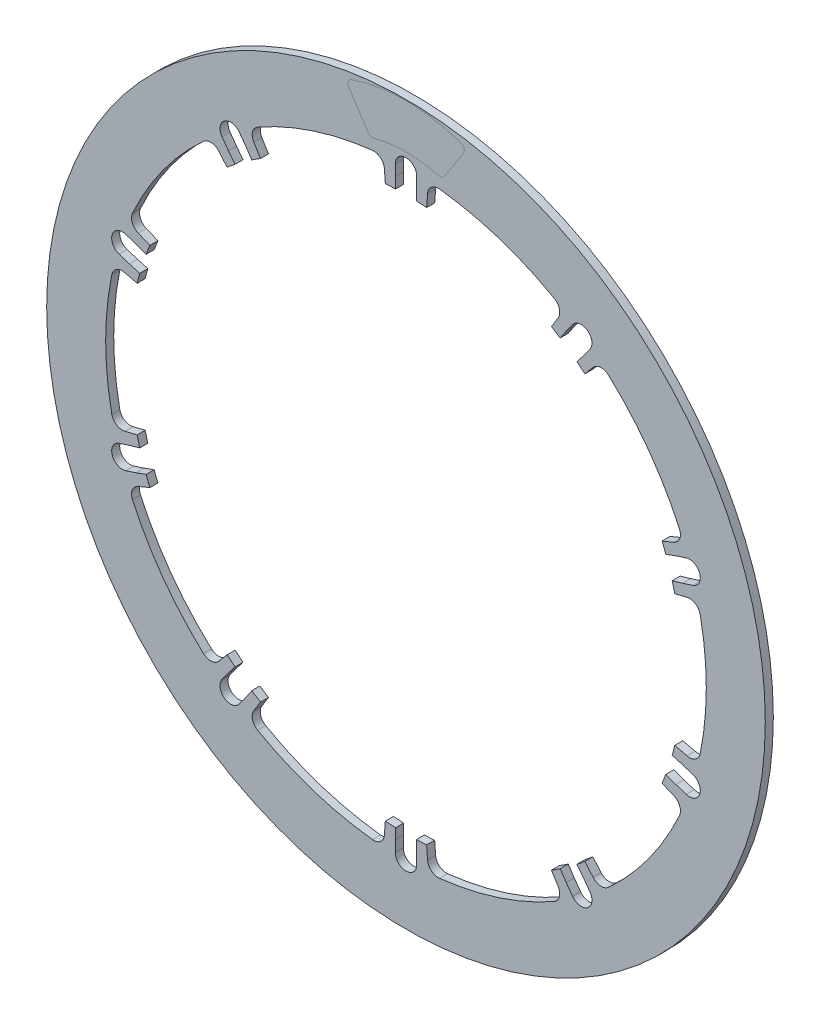
SolidWorks part; units mm, degrees
material "Gray Cast Iron"
ref_plane "Front Plane" through (0, 0, 0) normal (0, 0, 1) x (1, 0, 0)
ref_plane "Top Plane" through (0, 0, 0) normal (0, 1, 0) x (1, 0, 0)
ref_plane "Right Plane" through (0, 0, 0) normal (1, 0, 0) x (0, 0, -1)
sketch "Sketch1" plane through (0, 0, 0) normal (0, 0, 1) x (1, 0, 0)
  circle A0 centre (0, 0) radius 212.725
  dimension "D1" = 425.45
extrude "Boss-Extrude1" add sketch "Sketch1" along normal blind 4.7625
sketch3d "3DSketch3" [suppressed]
  line L4 (22.632, 184.3324, 30.7403) -> (33.9015, 201.686, 30.7403)
  line L5 (-33.9015, 201.686, 30.7403) -> (-22.632, 184.3324, 30.7403)
  arc A2 (-19.1346, 182.9983, 30.7403) -> (19.1346, 182.9983, 30.7403) centre (0, 112.7617, 30.7403) ccw
  spline S10 degree 3 poles (-22.632, 184.3324, 30.7403) (-22.5988, 184.2811, 30.7403) (-22.5293, 184.1805, 30.7403) (-22.4165, 184.0361, 30.7403) (-22.2957, 183.8983, 30.7403) (-22.1669, 183.7678, 30.7403) (-22.0309, 183.6449, 30.7403) (-21.8881, 183.53, 30.7403) (-21.7389, 183.4235, 30.7403) (-21.5838, 183.3258, 30.7403) (-21.4233, 183.2372, 30.7403) (-21.258, 183.1581, 30.7403) (-21.0428, 183.0698, 30.7403) (-20.7737, 182.9843, 30.7403) (-20.4488, 182.9172, 30.7403) (-20.1187, 182.8844, 30.7403) (-19.7871, 182.8865, 30.7403) (-19.4572, 182.9221, 30.7403) (-19.2411, 182.9691, 30.7403) (-19.1346, 182.9983, 30.7403) knots 0 0 0 0 0.045782 0.091558 0.137334 0.183113 0.228892 0.274672 0.32045 0.366227 0.412004 0.457782 0.503559 0.586301 0.669039 0.751777 0.834518 0.917255 1 1 1 1
  spline S11 degree 3 poles (19.1346, 182.9983, 30.7403) (19.1932, 182.9822, 30.7403) (19.3112, 182.9536, 30.7403) (19.4903, 182.9212, 30.7403) (19.6709, 182.8988, 30.7403) (19.8526, 182.8871, 30.7403) (20.0347, 182.8856, 30.7403) (20.2165, 182.8946, 30.7403) (20.3976, 182.9139, 30.7403) (20.5772, 182.9436, 30.7403) (20.7548, 182.9836, 30.7403) (20.9299, 183.0336, 30.7403) (21.1494, 183.1103, 30.7403) (21.4086, 183.2251, 30.7403) (21.6981, 183.3917, 30.7403) (21.9686, 183.5877, 30.7403) (22.2165, 183.8112, 30.7403) (22.4407, 184.059, 30.7403) (22.5716, 184.239, 30.7403) (22.632, 184.3324, 30.7403) knots 0 0 0 0 0.045473 0.090941 0.136409 0.181879 0.227351 0.272822 0.318291 0.36376 0.409229 0.454698 0.500168 0.583473 0.666777 0.750082 0.83339 0.916693 1 1 1 1
  spline S12 degree 3 poles (33.9015, 201.686, 30.7403) (33.9344, 201.7364, 30.7403) (33.9971, 201.839, 30.7403) (34.0817, 201.9976, 30.7403) (34.1575, 202.1609, 30.7403) (34.2237, 202.3283, 30.7403) (34.2804, 202.4992, 30.7403) (34.3274, 202.6731, 30.7403) (34.3646, 202.8492, 30.7403) (34.3917, 203.0273, 30.7403) (34.4086, 203.2065, 30.7403) (34.4153, 203.3864, 30.7403) (34.4119, 203.5665, 30.7403) (34.3756, 204.0435, 30.7403) (34.1614, 204.8075, 30.7403) (33.6821, 205.4852, 30.7403) (33.2752, 205.8566, 30.7403) (33.0454, 206.0314, 30.7403) (32.8006, 206.1843, 30.7403) (32.5436, 206.3149, 30.7403) (32.3643, 206.3858, 30.7403) (32.2732, 206.417, 30.7403) knots 0 0 0 0 0.031297 0.062588 0.093878 0.12517 0.156463 0.187756 0.219048 0.250339 0.28163 0.312921 0.344212 0.375504 0.562427 0.749344 0.799474 0.849606 0.899737 0.949865 1 1 1 1
  spline S13 degree 3 poles (32.2732, 206.417, 30.7403) (31.9592, 206.5252, 30.7403) (31.3303, 206.7384, 30.7403) (30.3838, 207.0486, 30.7403) (29.4343, 207.3495, 30.7403) (28.4817, 207.6406, 30.7403) (27.5262, 207.9222, 30.7403) (26.568, 208.1942, 30.7403) (25.6071, 208.4564, 30.7403) (24.6436, 208.7091, 30.7403) (23.6776, 208.952, 30.7403) (22.7092, 209.1852, 30.7403) (21.7385, 209.4087, 30.7403) (20.7656, 209.6224, 30.7403) (19.7906, 209.8263, 30.7403) (18.8136, 210.0204, 30.7403) (17.8348, 210.2046, 30.7403) (16.8541, 210.3791, 30.7403) (15.8717, 210.5436, 30.7403) (14.8877, 210.6982, 30.7403) (13.9022, 210.843, 30.7403) (12.9153, 210.9778, 30.7403) (11.927, 211.1027, 30.7403) (9.4532, 211.3901, 30.7403) (5.4798, 211.7206, 30.7403) (0, 211.8722, 30.7403) (-5.4798, 211.7206, 30.7403) (-9.7842, 211.3626, 30.7403) (-12.9159, 210.9828, 30.7403) (-14.8884, 210.7032, 30.7403) (-16.8549, 210.384, 30.7403) (-18.8146, 210.0253, 30.7403) (-20.7667, 209.6273, 30.7403) (-22.7103, 209.1901, 30.7403) (-24.6448, 208.7139, 30.7403) (-26.5694, 208.1991, 30.7403) (-28.483, 207.645, 30.7403) (-30.3853, 207.0535, 30.7403) (-31.6453, 206.6334, 30.7403) (-32.2732, 206.417, 30.7403) knots 0 0 0 0 0.015151 0.030302 0.045452 0.060603 0.075754 0.090905 0.106056 0.121206 0.136357 0.151508 0.166659 0.18181 0.19696 0.212111 0.227262 0.242413 0.257563 0.272714 0.287865 0.303016 0.318167 0.333317 0.41666 0.500002 0.583344 0.666687 0.696988 0.727289 0.75759 0.787892 0.818193 0.848494 0.878795 0.909096 0.939398 0.969699 1 1 1 1
  spline S14 degree 3 poles (-32.2732, 206.417, 30.7403) (-32.33, 206.3976, 30.7403) (-32.4424, 206.3554, 30.7403) (-32.6063, 206.2826, 30.7403) (-32.7663, 206.2007, 30.7403) (-32.9213, 206.1097, 30.7403) (-33.071, 206.0102, 30.7403) (-33.2148, 205.9024, 30.7403) (-33.3523, 205.7867, 30.7403) (-33.4831, 205.6634, 30.7403) (-33.6067, 205.5329, 30.7403) (-33.7226, 205.3956, 30.7403) (-33.8307, 205.2519, 30.7403) (-34.0967, 204.8533, 30.7403) (-34.3994, 204.1174, 30.7403) (-34.4385, 203.2861, 30.7403) (-34.346, 202.7423, 30.7403) (-34.2724, 202.4636, 30.7403) (-34.1736, 202.193, 30.7403) (-34.0515, 201.9325, 30.7403) (-33.9541, 201.7665, 30.7403) (-33.9015, 201.686, 30.7403) knots 0 0 0 0 0.031241 0.062476 0.093711 0.124947 0.156184 0.187421 0.218658 0.249893 0.281128 0.312363 0.343599 0.374835 0.562326 0.749809 0.799846 0.849885 0.899924 0.949958 1 1 1 1
  point P8 (0, 112.7617, -42.0561)
sketch "Sketch4" plane through (0, 0, 4.7625) normal (0, 0, 1) x (1, 0, 0)
  line L2 (22.7365, 184.6731) -> (34.006, 202.0267)
  line L3 (-33.7971, 202.0267) -> (-22.5275, 184.6731)
  arc A1 (19.2391, 183.339) -> (-19.0302, 183.339) centre (0.1045, 113.1023) ccw
  spline S5 degree 3 poles (34.006, 202.0267) (34.0389, 202.0771) (34.1016, 202.1797) (34.1862, 202.3383) (34.262, 202.5016) (34.3282, 202.669) (34.4038, 202.8969) (34.46, 203.1306) (34.4962, 203.3679) (34.5131, 203.5472) (34.5198, 203.7271) (34.5163, 203.9072) (34.4801, 204.3842) (34.2659, 205.1481) (33.7866, 205.8259) (33.3797, 206.1973) (33.1498, 206.3721) (32.9051, 206.525) (32.648, 206.6556) (32.4688, 206.7265) (32.3776, 206.7577) knots 0 0 0 0 0.031297 0.062588 0.093878 0.12517 0.156463 0.219048 0.250339 0.28163 0.312921 0.344212 0.375504 0.562427 0.749344 0.799474 0.849606 0.899737 0.949865 1 1 1 1
  spline S6 degree 3 poles (19.2391, 183.339) (19.2977, 183.3229) (19.4156, 183.2943) (19.5948, 183.2619) (19.7754, 183.2395) (19.9571, 183.2278) (20.1392, 183.2263) (20.321, 183.2353) (20.5021, 183.2546) (20.7416, 183.2942) (20.9771, 183.3543) (21.2539, 183.451) (21.5131, 183.5658) (21.8026, 183.7323) (22.073, 183.9284) (22.321, 184.1519) (22.5452, 184.3996) (22.6761, 184.5797) (22.7365, 184.6731) knots 0 0 0 0 0.045473 0.090941 0.136409 0.181879 0.227351 0.272822 0.318291 0.36376 0.454698 0.500168 0.583473 0.666777 0.750082 0.83339 0.916693 1 1 1 1
  spline S7 degree 3 poles (-22.5275, 184.6731) (-22.4943, 184.6218) (-22.4249, 184.5212) (-22.312, 184.3768) (-22.1912, 184.239) (-22.0624, 184.1085) (-21.9264, 183.9856) (-21.7836, 183.8707) (-21.6344, 183.7642) (-21.4276, 183.6339) (-21.2101, 183.5219) (-20.9383, 183.4105) (-20.6692, 183.325) (-20.3444, 183.2579) (-20.0142, 183.225) (-19.6827, 183.2272) (-19.3527, 183.2628) (-19.1367, 183.3098) (-19.0302, 183.339) knots 0 0 0 0 0.045782 0.091558 0.137334 0.183113 0.228892 0.274672 0.32045 0.366227 0.457782 0.503559 0.586301 0.669039 0.751777 0.834518 0.917255 1 1 1 1
  spline S8 degree 3 poles (-32.1687, 206.7577) (-32.2255, 206.7383) (-32.3379, 206.6961) (-32.5019, 206.6233) (-32.6618, 206.5414) (-32.8168, 206.4504) (-33.0164, 206.3177) (-33.2043, 206.1685) (-33.3786, 206.0041) (-33.5022, 205.8736) (-33.6182, 205.7363) (-33.7262, 205.5926) (-33.9922, 205.194) (-34.2949, 204.4581) (-34.3341, 203.6268) (-34.2415, 203.083) (-34.1679, 202.8043) (-34.0691, 202.5337) (-33.947, 202.2732) (-33.8496, 202.1072) (-33.7971, 202.0267) knots 0 0 0 0 0.031241 0.062476 0.093711 0.124947 0.156184 0.218658 0.249893 0.281128 0.312363 0.343599 0.374835 0.562326 0.749809 0.799846 0.849885 0.899924 0.949958 1 1 1 1
  spline S9 degree 3 poles (32.3776, 206.7577) (32.0637, 206.8659) (31.4348, 207.0791) (30.4883, 207.3893) (29.5388, 207.6902) (28.5862, 207.9813) (26.9938, 208.4506) (23.7904, 209.325) (20.2255, 210.1269) (16.6328, 210.7845) (14.6646, 211.0938) (13.0197, 211.3185) (12.0315, 211.4434) (9.5577, 211.7308) (5.5843, 212.0613) (0.1045, 212.2129) (-5.3753, 212.0613) (-9.6798, 211.7033) (-12.8114, 211.3235) (-14.7839, 211.0439) (-16.7504, 210.7247) (-18.7101, 210.366) (-20.6622, 209.968) (-22.6058, 209.5308) (-24.5403, 209.0546) (-26.4649, 208.5398) (-28.3785, 207.9857) (-30.2808, 207.3942) (-31.5409, 206.9741) (-32.1687, 206.7577) knots 0 0 0 0 0.015151 0.030302 0.045452 0.060603 0.075754 0.121206 0.212111 0.242413 0.287865 0.303016 0.318167 0.333317 0.41666 0.500002 0.583344 0.666687 0.696988 0.727289 0.75759 0.787892 0.818193 0.848494 0.878795 0.909096 0.939398 0.969699 1 1 1 1
sketch "Sketch6" plane through (0, 0, 0) normal (0, 0, -1) x (-1, 0, 0)
  line L0 (-22.7365, 184.6731) -> (-34.006, 202.0267) construction
  line L1 (33.7971, 202.0267) -> (22.5275, 184.6731) construction
  line L2 (-22.7365, 184.6731) -> (-34.006, 202.0267)
  line L3 (33.7971, 202.0267) -> (22.5275, 184.6731)
  arc A0 (19.0302, 183.339) -> (-19.2391, 183.339) centre (-0.1045, 113.1023) ccw construction
  circle A1 centre (0, 0) radius 212.725
  circle A2 centre (0, 0) radius 212.725
  arc A3 (19.0302, 183.339) -> (-19.2391, 183.339) centre (-0.1045, 113.1023) ccw
  spline S0 degree 3 poles (-2016.3209, 153.4131) (-13.1774, 313.7756) (-3.6105, 186.1555) (-19.5948, 183.2619) (-19.7754, 183.2395) (-19.9571, 183.2278) (-20.1392, 183.2263) (-20.321, 183.2353) (-20.5021, 183.2546) (-20.7416, 183.2942) (-20.9771, 183.3543) (-21.2539, 183.451) (-21.5131, 183.5658) (-21.8026, 183.7323) (-22.073, 183.9284) (-22.321, 184.1519) (-33.7349, 196.7661) (61.8944, 295.2324) (1583.0626, -1002.353) knots -12.036429 -12.036429 -12.036429 -12.036429 0.045473 0.090941 0.136409 0.181879 0.227351 0.272822 0.318291 0.36376 0.454698 0.500168 0.583473 0.666777 0.750082 0.83339 0.916693 13.47468 13.47468 13.47468 13.47468 only from (-19.2391, 183.339) to (-22.7365, 184.6731) construction
  spline S1 degree 3 poles (-741.6985, 2071.3636) (51.5513, 215.3428) (-28.083, 190.8965) (-34.1862, 202.3383) (-34.262, 202.5016) (-34.3282, 202.669) (-34.4038, 202.8969) (-34.46, 203.1306) (-34.4962, 203.3679) (-34.5131, 203.5472) (-34.5198, 203.7271) (-34.5163, 203.9072) (-34.4801, 204.3842) (-34.2659, 205.1481) (-33.7866, 205.8259) (-33.3797, 206.1973) (-33.1498, 206.3721) (-32.9051, 206.525) (-19.4783, 213.3465) (41.9008, 122.514) (-1615.5521, -1012.0405) knots -6.679954 -6.679954 -6.679954 -6.679954 0.031297 0.062588 0.093878 0.12517 0.156463 0.219048 0.250339 0.28163 0.312921 0.344212 0.375504 0.562427 0.749344 0.799474 0.849606 0.899737 0.949865 8.706653 8.706653 8.706653 8.706653 only from (-34.006, 202.0267) to (-32.3776, 206.7577) construction
  spline S2 degree 3 poles (1661.243, 1259.3746) (-203.7859, -162.5293) (-163.0238, 163.9576) (-30.4883, 207.3893) (-29.5388, 207.6902) (-28.5862, 207.9813) (-26.9938, 208.4506) (-23.7904, 209.325) (-20.2255, 210.1269) (-16.6328, 210.7845) (-14.6646, 211.0938) (-13.0197, 211.3185) (-12.0315, 211.4434) (-9.5577, 211.7308) (-5.5843, 212.0613) (-0.1045, 212.2129) (5.3753, 212.0613) (9.6798, 211.7033) (12.8114, 211.3235) (14.7839, 211.0439) (16.7504, 210.7247) (18.7101, 210.366) (20.6622, 209.968) (22.6058, 209.5308) (24.5403, 209.0546) (26.4649, 208.5398) (28.3785, 207.9857) (189.3327, 157.9434) (218.1983, -304.2931) (-1891.4217, 643.6889) knots -6.319065 -6.319065 -6.319065 -6.319065 0.015151 0.030302 0.045452 0.060603 0.075754 0.121206 0.212111 0.242413 0.287865 0.303016 0.318167 0.333317 0.41666 0.500002 0.583344 0.666687 0.696988 0.727289 0.75759 0.787892 0.818193 0.848494 0.878795 0.909096 0.939398 0.969699 8.600273 8.600273 8.600273 8.600273 only from (-32.3776, 206.7577) to (32.1687, 206.7577) construction
  spline S3 degree 3 poles (1741.3262, -829.6052) (-26.9574, 143.7974) (20.6648, 211.8759) (32.5019, 206.6233) (32.6618, 206.5414) (32.8168, 206.4504) (33.0164, 206.3177) (33.2043, 206.1685) (33.3786, 206.0041) (33.5022, 205.8736) (33.6182, 205.7363) (33.7262, 205.5926) (33.9922, 205.194) (34.2949, 204.4581) (34.3341, 203.6268) (34.2415, 203.083) (34.1679, 202.8043) (34.0691, 202.5337) (27.687, 188.9067) (-76.4304, 222.6453) (533.1826, 2136.6237) knots -6.671073 -6.671073 -6.671073 -6.671073 0.031241 0.062476 0.093711 0.124947 0.156184 0.218658 0.249893 0.281128 0.312363 0.343599 0.374835 0.562326 0.749809 0.799846 0.849885 0.899924 0.949958 8.70048 8.70048 8.70048 8.70048 only from (32.1687, 206.7577) to (33.7971, 202.0267) construction
  spline S4 degree 3 poles (-1450.1633, -1164.7301) (-59.0763, 285.4864) (32.2795, 197.129) (22.312, 184.3768) (22.1912, 184.239) (22.0624, 184.1085) (21.9264, 183.9856) (21.7836, 183.8707) (21.6344, 183.7642) (21.4276, 183.6339) (21.2101, 183.5219) (20.9383, 183.4105) (20.6692, 183.325) (20.3444, 183.2579) (20.0142, 183.225) (19.6827, 183.2272) (2.7527, 185.055) (8.5785, 322.4741) (2007.8128, 363.0309) knots -11.991769 -11.991769 -11.991769 -11.991769 0.045782 0.091558 0.137334 0.183113 0.228892 0.274672 0.32045 0.366227 0.457782 0.503559 0.586301 0.669039 0.751777 0.834518 0.917255 13.489507 13.489507 13.489507 13.489507 only from (22.5275, 184.6731) to (19.0302, 183.339) construction
  spline S5 degree 3 poles (-19.2391, 183.339) (-19.2977, 183.3229) (-19.4156, 183.2943) (-19.5948, 183.2619) (-19.7754, 183.2395) (-19.9571, 183.2278) (-20.1392, 183.2263) (-20.321, 183.2353) (-20.5021, 183.2546) (-20.7416, 183.2942) (-20.9771, 183.3543) (-21.2539, 183.451) (-21.5131, 183.5658) (-21.8026, 183.7323) (-22.073, 183.9284) (-22.321, 184.1519) (-22.5452, 184.3996) (-22.6761, 184.5797) (-22.7365, 184.6731) knots 0 0 0 0 0.045473 0.090941 0.136409 0.181879 0.227351 0.272822 0.318291 0.36376 0.454698 0.500168 0.583473 0.666777 0.750082 0.83339 0.916693 1 1 1 1
  spline S6 degree 3 poles (-34.006, 202.0267) (-34.0389, 202.0771) (-34.1016, 202.1797) (-34.1862, 202.3383) (-34.262, 202.5016) (-34.3282, 202.669) (-34.4038, 202.8969) (-34.46, 203.1306) (-34.4962, 203.3679) (-34.5131, 203.5472) (-34.5198, 203.7271) (-34.5163, 203.9072) (-34.4801, 204.3842) (-34.2659, 205.1481) (-33.7866, 205.8259) (-33.3797, 206.1973) (-33.1498, 206.3721) (-32.9051, 206.525) (-32.648, 206.6556) (-32.4688, 206.7265) (-32.3776, 206.7577) knots 0 0 0 0 0.031297 0.062588 0.093878 0.12517 0.156463 0.219048 0.250339 0.28163 0.312921 0.344212 0.375504 0.562427 0.749344 0.799474 0.849606 0.899737 0.949865 1 1 1 1
  spline S7 degree 3 poles (-32.3776, 206.7577) (-32.0637, 206.8659) (-31.4348, 207.0791) (-30.4883, 207.3893) (-29.5388, 207.6902) (-28.5862, 207.9813) (-26.9938, 208.4506) (-23.7904, 209.325) (-20.2255, 210.1269) (-16.6328, 210.7845) (-14.6646, 211.0938) (-13.0197, 211.3185) (-12.0315, 211.4434) (-9.5577, 211.7308) (-5.5843, 212.0613) (-0.1045, 212.2129) (5.3753, 212.0613) (9.6798, 211.7033) (12.8114, 211.3235) (14.7839, 211.0439) (16.7504, 210.7247) (18.7101, 210.366) (20.6622, 209.968) (22.6058, 209.5308) (24.5403, 209.0546) (26.4649, 208.5398) (28.3785, 207.9857) (30.2808, 207.3942) (31.5409, 206.9741) (32.1687, 206.7577) knots 0 0 0 0 0.015151 0.030302 0.045452 0.060603 0.075754 0.121206 0.212111 0.242413 0.287865 0.303016 0.318167 0.333317 0.41666 0.500002 0.583344 0.666687 0.696988 0.727289 0.75759 0.787892 0.818193 0.848494 0.878795 0.909096 0.939398 0.969699 1 1 1 1
  spline S8 degree 3 poles (32.1687, 206.7577) (32.2255, 206.7383) (32.3379, 206.6961) (32.5019, 206.6233) (32.6618, 206.5414) (32.8168, 206.4504) (33.0164, 206.3177) (33.2043, 206.1685) (33.3786, 206.0041) (33.5022, 205.8736) (33.6182, 205.7363) (33.7262, 205.5926) (33.9922, 205.194) (34.2949, 204.4581) (34.3341, 203.6268) (34.2415, 203.083) (34.1679, 202.8043) (34.0691, 202.5337) (33.947, 202.2732) (33.8496, 202.1072) (33.7971, 202.0267) knots 0 0 0 0 0.031241 0.062476 0.093711 0.124947 0.156184 0.218658 0.249893 0.281128 0.312363 0.343599 0.374835 0.562326 0.749809 0.799846 0.849885 0.899924 0.949958 1 1 1 1
  spline S9 degree 3 poles (22.5275, 184.6731) (22.4943, 184.6218) (22.4249, 184.5212) (22.312, 184.3768) (22.1912, 184.239) (22.0624, 184.1085) (21.9264, 183.9856) (21.7836, 183.8707) (21.6344, 183.7642) (21.4276, 183.6339) (21.2101, 183.5219) (20.9383, 183.4105) (20.6692, 183.325) (20.3444, 183.2579) (20.0142, 183.225) (19.6827, 183.2272) (19.3527, 183.2628) (19.1367, 183.3098) (19.0302, 183.339) knots 0 0 0 0 0.045782 0.091558 0.137334 0.183113 0.228892 0.274672 0.32045 0.366227 0.457782 0.503559 0.586301 0.669039 0.751777 0.834518 0.917255 1 1 1 1
  dimension "D1" = 0
sketch "Sketch8" plane through (0, 0, 0) normal (0, 0, -1) x (-1, 0, 0)
  circle A0 centre (0, 0) radius 170.18
  dimension "D1" = 340.36
extrude "Cut-Extrude1" cut sketch "Sketch8" against normal up to surface (4.7625 mm away) up to face at (212.725, 0, 4.7625)
sketch "Sketch9" plane through (0, 0, 0) normal (0, 0, -1) x (-1, 0, 0)
  line L1 (-6.35, 163.83) -> (6.35, 163.83)
  line L2 (-6.35, 163.83) -> (-6.35, 176.53)
  line L3 (-6.35, 176.53) -> (6.35, 176.53)
  line L4 (6.35, 163.83) -> (6.35, 176.53)
  line L5 (-6.35, 163.83) -> (6.35, 176.53) construction
  line L6 (-6.35, 176.53) -> (6.35, 163.83) construction
  circle A0 centre (0, 0) radius 170.18 construction
  circle A1 centre (0, 176.53) radius 6.35
  point P0 (0, 170.18)
  circle M4 centre (0, 0) radius 170.18
  dimension "D1" = 12.7
  dimension "D2" = 12.7
extrude "Cut-Extrude3" cut sketch "Sketch9" along direction (0, 0, 1) on the side against the normal up to surface (4.7625 mm away) contours L3 A1 | L3 A1 | A1 L4 M4 | A1 L2 M4
pattern_circular "CirPattern1" count 10 every 36 about axis through (0, 0, 0) along (0, 0, 1) of "Cut-Extrude3"
sketch "Sketch11" plane through (0, 0, 4.7625) normal (0, 0, 1) x (1, 0, 0)
  line L0 (-12.2165, 163.3739) -> (-12.4992, 167.1541)
  line L1 (-6.35, 170.0615) -> (-6.1131, 163.7159)
  line L2 (6.1131, 163.7159) -> (6.35, 170.0615)
  line L3 (12.2261, 163.3732) -> (12.509, 167.1534)
  arc A0 (12.2261, 163.3732) -> (6.1131, 163.7159) centre (0, 0) ccw
  arc A1 (-6.35, 170.0615) -> (-94.8224, 141.3151) centre (0, 0) ccw construction
  arc A2 (94.8224, 141.3151) -> (6.35, 170.0615) centre (0, 0) ccw construction
  arc A3 (-6.1131, 163.7159) -> (-12.2165, 163.3739) centre (0, 0) ccw
  arc A4 (-15.2599, 169.4944) -> (-94.8224, 141.3151) centre (0, 0) ccw
  arc A5 (94.8224, 141.3151) -> (15.2698, 169.4936) centre (0, 0) ccw
  arc A6 (-15.2599, 169.4944) -> (-12.4992, 167.1541) centre (-15.0321, 166.9647) cw
  arc A7 (15.2698, 169.4936) -> (12.509, 167.1534) centre (15.0419, 166.9638) ccw
  arc M5 (-94.8224, 141.3151) -> (-6.35, 170.0615) centre (0, 0) cw
  arc M9 (6.35, 170.0615) -> (94.8224, 141.3151) centre (0, 0) cw
  dimension "D1" = 327.66
  dimension "D2" = 2.54
  dimension "D3" = 2.54
extrude "Boss-Extrude2" add sketch "Sketch11" against normal up to surface (4.7625 mm away) contours A0 L3 L2 M9 | A3 L1 L0 M5 up to face at (0, 0, 0)
pattern_circular "CirPattern2" count 10 every 36 about axis through (0, 0, 0) along (0, 0, 1) of "Boss-Extrude2"
split line "Split Line1"
split line "Split Line2"
sketch "Sketch15" plane through (0, 0, 4.7625) normal (0, 0, 1) x (1, 0, 0)
  line L0 (-12.2165, 163.3739) -> (12.2261, 163.3732)
sketch "Sketch17" plane through (0, 0, 4.7625) normal (0, 0, 1) x (1, 0, 0)
  line L0 (0, 0) -> (110.7699, 130.7089)
  line L1 (0, 0) -> (158.5451, 64.9479)
  arc A0 (161.9209, 73.4471) -> (119.8963, 131.2925) centre (0, 0) ccw
  arc A1 (161.9209, 73.4471) -> (158.5451, 64.9479) centre (156.138, 70.824) cw
  arc A2 (110.7699, 130.7089) -> (119.8963, 131.2925) centre (115.6143, 126.6035) cw
  dimension "D1" = 0
  dimension "D3" = 6.35
  dimension "D4" = 6.35
  dimension "D2" = 0
extrude "Cut-Extrude4" cut sketch "Sketch17" against normal up to surface (4.7625 mm away) up to face at (212.725, 0, 0)
pattern_circular "CirPattern3" count 10 every 36 about axis through (0, 0, 0) along (0, 0, 1) of "Cut-Extrude4"
sketch "Sketch18" plane through (0, 0, 4.7625) normal (0, 0, 1) x (1, 0, 0)
  circle A0 centre (0, 0) radius 210.8834 construction
